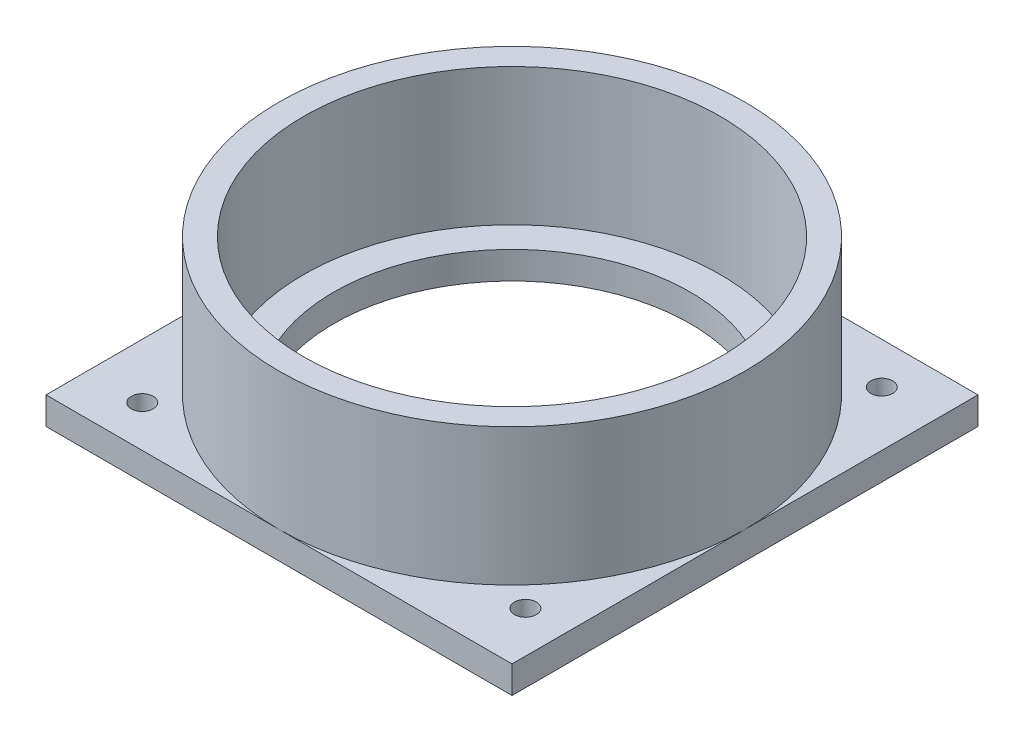
SolidWorks part; units mm, degrees
ref_plane "Ön Düzlem" through (0, 0, 0) normal (0, 0, 1) x (1, 0, 0)
ref_plane "Üst Düzlem" through (0, 0, 0) normal (0, 1, 0) x (1, 0, 0)
ref_plane "Sağ Düzlem" through (0, 0, 0) normal (1, 0, 0) x (0, 0, -1)
sketch "Çizim1" plane through (0, 0, 0) normal (0, 1, 0) x (1, 0, 0)
  line L1 (-42.5, 42.5) -> (42.5, 42.5)
  line L2 (-42.5, 42.5) -> (-42.5, -42.5)
  line L3 (-42.5, -42.5) -> (42.5, -42.5)
  line L4 (42.5, 42.5) -> (42.5, -42.5)
  line L5 (-42.5, 42.5) -> (42.5, -42.5) construction
  line L6 (-42.5, -42.5) -> (42.5, 42.5) construction
  point P0 (0, 0)
extrude "Yükseklik-Ekstrüzyon1" add sketch "Çizim1" along normal blind 5
sketch "Çizim2" plane through (0, 5, 0) normal (0, 1, 0) x (1, 0, 0)
  circle A0 centre (0, 0) radius 32.5
extrude "Kes-Ekstrüzyon1" cut sketch "Çizim2" against normal blind 5
sketch "Çizim3" plane through (0, 5, 0) normal (0, 1, 0) x (1, 0, 0)
  circle A0 centre (0, 0) radius 38
  circle A1 centre (0, 0) radius 42.5
  dimension "D1" = 76
extrude "Yükseklik-Ekstrüzyon2" add sketch "Çizim3" along normal blind 25
sketch "Çizim4" plane through (0, 5, 0) normal (0, 1, 0) x (1, 0, 0)
  circle A1 centre (-34.9431, 32.5) radius 2
  circle A2 centre (32.5, 34.9431) radius 2
  circle A3 centre (34.9431, -32.5) radius 2
  circle A4 centre (-32.5, -34.9431) radius 2
  dimension "D1" = 4
extrude "Kes-Ekstrüzyon2" cut sketch "Çizim4" against normal blind 25
